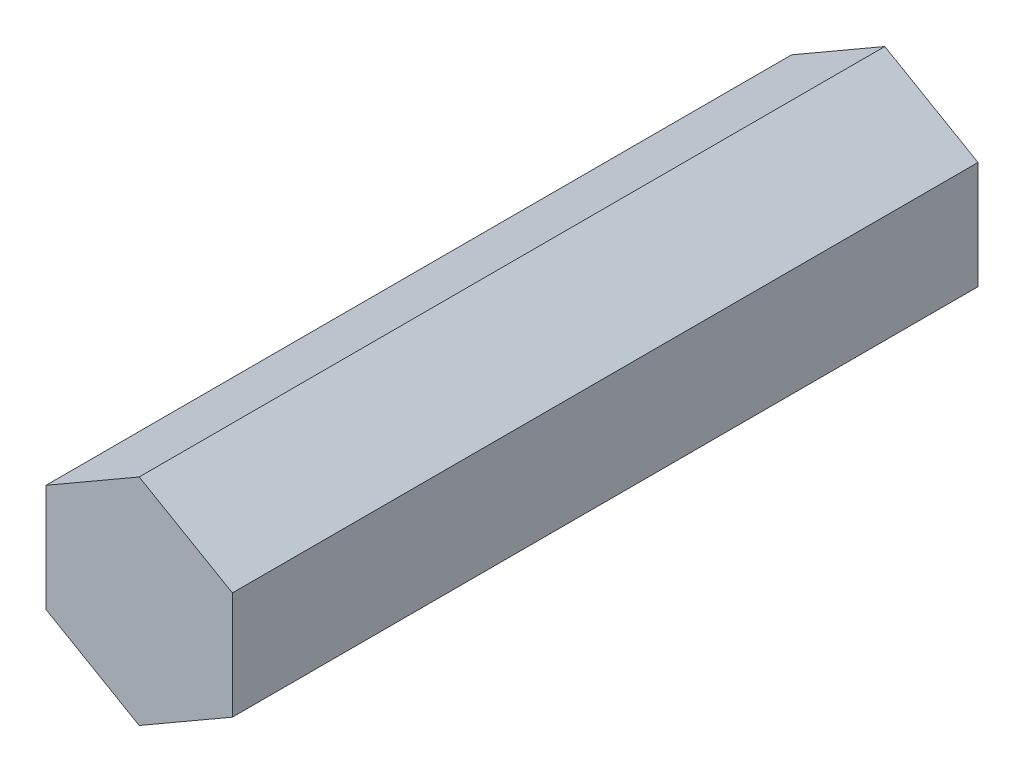
SolidWorks part; units mm, degrees
ref_plane "Front Plane" through (0, 0, 0) normal (0, 0, 1) x (1, 0, 0)
ref_plane "Top Plane" through (0, 0, 0) normal (0, 1, 0) x (1, 0, 0)
ref_plane "Right Plane" through (0, 0, 0) normal (1, 0, 0) x (0, 0, -1)
sketch "Sketch1" plane through (0, 0, 0) normal (0, 0, 1) x (1, 0, 0)
  line L1 (-6.35, -3.6662) -> (0, -7.3323)
  line L2 (0, -7.3323) -> (6.35, -3.6662)
  line L3 (6.35, -3.6662) -> (6.35, 3.6662)
  line L4 (6.35, 3.6662) -> (0, 7.3323)
  line L5 (0, 7.3323) -> (-6.35, 3.6662)
  line L6 (-6.35, 3.6662) -> (-6.35, -3.6662)
  circle A0 centre (0, 0) radius 6.35 construction
  dimension "D1" = 12.7
extrude "Boss-Extrude1" add sketch "Sketch1" along normal blind 50.8
